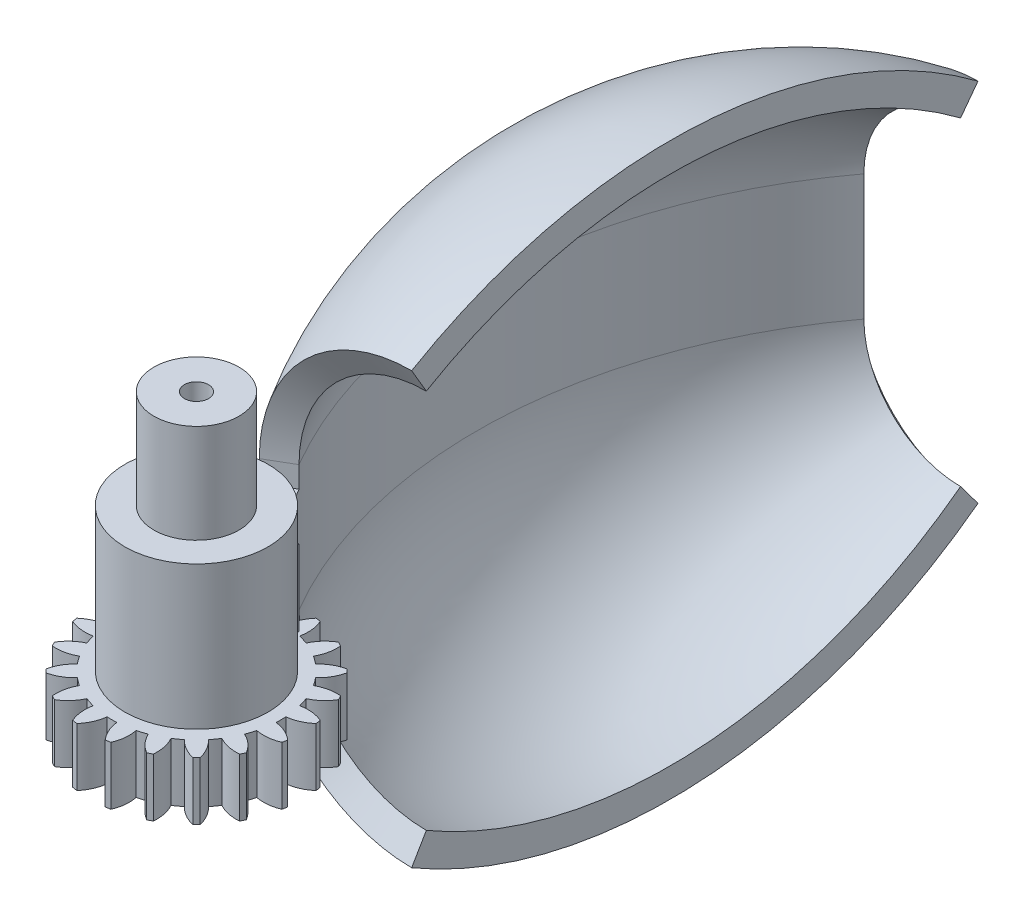
SolidWorks part; units mm, degrees
ref_plane "前视基准面" through (0, 0, 0) normal (0, 0, 1) x (1, 0, 0)
ref_plane "上视基准面" through (0, 0, 0) normal (0, 1, 0) x (1, 0, 0)
ref_plane "右视基准面" through (0, 0, 0) normal (1, 0, 0) x (0, 0, -1)
sketch "草图1" plane through (0, 0, 0) normal (0, 1, 0) x (1, 0, 0)
  line L0 (0, 0) -> (40, 0) construction
  line L1 (0, 42.7058) -> (0, -47.7896) construction
  line L2 (40, 0) -> (0, 30) construction
  line L3 (40, 0) -> (0, -30) construction
  line L4 (-2.4, 31.8) -> (0, 30)
  arc A0 (0, 30) -> (-1.3669, -28.0853) centre (40, 0) ccw
  arc A1 (-2.4, 31.8) -> (-5.7538, -26.7505) centre (40, 0) ccw
  arc A2 (-6.4737, -32.7477) -> (1.7806, -30.1779) centre (0, -39) ccw
  arc A3 (-6.4737, -32.7477) -> (-5.7538, -26.7505) centre (-10.0702, -29.2742) ccw
  arc A4 (1.7806, -30.1779) -> (-1.3669, -28.0853) centre (2.7698, -25.2767) cw
  circle A5 centre (0, -39) radius 1.25
  point P18 (0, -30)
  dimension "D4" = 18
  dimension "D5" = 5
  dimension "D6" = 5
  dimension "D7" = 2.5
  dimension "D1" = 60
  dimension "D2" = 40
  dimension "D3" = 53
extrude "凸台-拉伸2" add sketch "草图1" along normal blind 3
sketch "草图2" plane through (0, 3, 0) normal (0, 1, 0) x (1, 0, 0)
  line L0 (40, 0) -> (-5.7538, -26.7505) construction
  line L1 (-5.7538, -26.7505) -> (-3.1639, -25.2364)
  line L2 (-2.4, 31.8) -> (0, 30)
  line L3 (40, 0) -> (10, 0) construction
  line L4 (10, 9.7418) -> (10, -18.4807) construction
  arc A1 (0, 30) -> (-1.3669, -28.0853) centre (40, 0) ccw construction
  arc A2 (-2.4, 31.8) -> (-5.7538, -26.7505) centre (40, 0) ccw construction
  arc A4 (0, 30) -> (-3.1639, -25.2364) centre (40, 0) ccw
  arc A5 (-2.4, 31.8) -> (-5.7538, -26.7505) centre (40, 0) ccw
  dimension "13" = 30
extrude "凸台-拉伸6" add sketch "草图2" along normal blind 10
sketch "草图3" plane through (0, 0, 0) normal (0, -1, 0) x (1, 0, 0)
  line L0 (0, -30) -> (-2.4, -31.8) construction
  line L1 (0, -30) -> (-2.4, -31.8)
  line L2 (40, 0) -> (-5.7538, 26.7505) construction
  line L3 (-5.7538, 26.7505) -> (-3.1639, 25.2364)
  line L4 (40, 0) -> (10, 0) construction
  line L5 (10, 8.9651) -> (10, -7.6873) construction
  arc A0 (-5.7538, 26.7505) -> (-2.4, -31.8) centre (40, 0) ccw construction
  arc A1 (-1.3669, 28.0853) -> (0, -30) centre (40, 0) ccw construction
  arc A2 (-5.7538, 26.7505) -> (-2.4, -31.8) centre (40, 0) ccw
  arc A3 (-3.1639, 25.2364) -> (0, -30) centre (40, 0) ccw
  dimension "D1" = 30
revolve "旋转5" add sketch "草图3" angle 90 about L5
sketch "草图5" plane through (0, 3, 0) normal (0, 1, 0) x (1, 0, 0)
  circle A0 centre (0, -39) radius 7.4
  circle A1 centre (0, -39) radius 1.25 construction
  circle A2 centre (0, -39) radius 1.25
  dimension "D1" = 14.8
extrude "凸台-拉伸3" add sketch "草图5" along normal blind 14.8
sketch "草图6" plane through (0, 17.8, 0) normal (0, 1, 0) x (1, 0, 0)
  circle A0 centre (0, -39) radius 4.4
  circle A2 centre (0, -39) radius 1.25 construction
  circle A3 centre (0, -39) radius 1.25
  dimension "D1" = 8.8
  dimension "D2" = 2.5
extrude "凸台-拉伸4" add sketch "草图6" along normal blind 10.2
sketch "草图8" plane through (0, 13, 0) normal (0, 1, 0) x (1, 0, 0)
  line L0 (40, 0) -> (10, 0) construction
  line L1 (10, 0) -> (10, 11.1191) construction
  line L2 (0, 30) -> (-2.4, 31.8)
  line L3 (-5.7538, -26.7505) -> (-3.1639, -25.2364)
  line L4 (0, 30) -> (-2.4, 31.8)
  line L5 (-5.7538, -26.7505) -> (-3.1639, -25.2364)
  arc A2 (0, 30) -> (-3.1639, -25.2364) centre (40, 0) ccw
  arc A3 (-2.4, 31.8) -> (-5.7538, -26.7505) centre (40, 0) ccw
  arc A4 (0, 30) -> (-3.1639, -25.2364) centre (40, 0) ccw
  arc A5 (-2.4, 31.8) -> (-5.7538, -26.7505) centre (40, 0) ccw
  dimension "D2" = 30
  dimension "D1" = 0
revolve "旋转6" add sketch "草图8" angle 90 about L1
sketch "草图9" plane through (0, 3, 0) normal (0, 1, 0) x (1, 0, 0)
  line L0 (-5.3339, -33.8708) -> (-6.4737, -32.7477)
  line L1 (-3.1639, -25.2364) -> (-5.7538, -26.7505)
  line L2 (-3.1639, -25.2364) -> (-5.7538, -26.7505)
  line L3 (1.4703, -31.7475) -> (1.7806, -30.1779)
  circle A0 centre (0, -39) radius 7.4 construction
  arc A1 (1.4703, -31.7475) -> (-5.3339, -33.8708) centre (0, -39) ccw
  arc A4 (-6.4737, -32.7477) -> (-5.7538, -26.7505) centre (-10.0702, -29.2742) ccw
  arc A5 (-6.4737, -32.7477) -> (1.7806, -30.1779) centre (0, -39) ccw
  arc A6 (-1.3669, -28.0853) -> (1.7806, -30.1779) centre (2.7698, -25.2767) ccw
  arc A7 (-3.1639, -25.2364) -> (-1.3669, -28.0853) centre (40, 0) ccw
  arc A8 (-6.4737, -32.7477) -> (-5.7538, -26.7505) centre (-10.0702, -29.2742) ccw
  arc A10 (-1.3669, -28.0853) -> (1.7806, -30.1779) centre (2.7698, -25.2767) ccw
  arc A11 (-3.1639, -25.2364) -> (-1.3669, -28.0853) centre (40, 0) ccw
  dimension "D1" = 0
extrude "凸台-拉伸7" add sketch "草图9" along normal blind 7.8
sketch "草图12" plane through (0, 0, 0) normal (0, -1, 0) x (1, 0, 0)
  line L4 (-6.4737, 32.7477) -> (0, 39)
  line L5 (0, 39) -> (1.7806, 30.1779)
  arc A4 (1.7806, 30.1779) -> (-6.4737, 32.7477) centre (0, 39) ccw construction
  arc A5 (1.7806, 30.1779) -> (-6.4737, 32.7477) centre (0, 39) ccw
extrude "切除-拉伸1" cut sketch "草图12" against normal blind 3
sketch "草图14" plane through (0, 0, 0) normal (0, -1, 0) x (1, 0, 0)
  line L0 (-6.4737, 32.7477) -> (1.7806, 30.1779)
  line L4 (1.7806, 30.1779) -> (0.2473, 37.7747)
  line L5 (-5.7538, 26.7505) -> (-3.1639, 25.2364)
  line L8 (-5.7538, 26.7505) -> (-3.1639, 25.2364)
  line L9 (1.7806, 30.1779) -> (0.2473, 37.7747) construction
  line L10 (-0.8991, 38.1316) -> (-6.4737, 32.7477)
  line L11 (-0.8991, 38.1316) -> (-6.4737, 32.7477) construction
  arc A4 (1.7806, 30.1779) -> (-1.3669, 28.0853) centre (2.7698, 25.2767) ccw
  arc A5 (-0.8991, 38.1316) -> (0.2473, 37.7747) centre (0, 39) ccw
  arc A6 (-5.7538, 26.7505) -> (-6.4737, 32.7477) centre (-10.0702, 29.2742) ccw
  arc A7 (-1.3669, 28.0853) -> (-3.1639, 25.2364) centre (40, 0) ccw
  arc A8 (1.7806, 30.1779) -> (-1.3669, 28.0853) centre (2.7698, 25.2767) ccw
  arc A10 (-5.7538, 26.7505) -> (-6.4737, 32.7477) centre (-10.0702, 29.2742) ccw
  arc A11 (-1.3669, 28.0853) -> (-3.1639, 25.2364) centre (40, 0) ccw
  arc A12 (-0.8991, 38.1316) -> (0.2473, 37.7747) centre (0, 39) ccw construction
  dimension "D1" = 0
extrude "凸台-拉伸9" add sketch "草图14" along normal blind 3
sketch "草图13" plane through (0, 0, 0) normal (0, -1, 0) x (1, 0, 0)
  arc A240 (1.465, 49.902) -> (0.4999, 47.7347) centre (4.4722, 47.2645) ccw
  arc A241 (0.4999, 47.7347) -> (-0.4999, 47.7347) centre (0, 39) ccw
  arc A242 (-0.4999, 47.7347) -> (-1.465, 49.902) centre (-4.4722, 47.2645) ccw
  arc A243 (-1.465, 49.902) -> (-1.9757, 49.8211) centre (0, 39) ccw
  arc A244 (-1.9757, 49.8211) -> (-2.2237, 47.4617) centre (1.6994, 48.242) ccw
  arc A245 (-2.2237, 47.4617) -> (-3.1746, 47.1527) centre (0, 39) ccw
  arc A246 (-3.1746, 47.1527) -> (-4.7622, 48.9157) centre (-6.8072, 45.478) ccw
  arc A247 (-4.7622, 48.9157) -> (-5.2229, 48.681) centre (0, 39) ccw
  arc A248 (-5.2229, 48.681) -> (-4.7297, 46.3604) centre (-1.2397, 48.3148) ccw
  arc A249 (-4.7297, 46.3604) -> (-5.5386, 45.7727) centre (0, 39) ccw
  arc A250 (-5.5386, 45.7727) -> (-7.5932, 46.9588) centre (-8.4758, 43.0574) ccw
  arc A251 (-7.5932, 46.9588) -> (-7.9588, 46.5932) centre (0, 39) ccw
  arc A252 (-7.9588, 46.5932) -> (-6.7727, 44.5386) centre (-4.0574, 47.4758) ccw
  arc A253 (-6.7727, 44.5386) -> (-7.3604, 43.7297) centre (0, 39) ccw
  arc A254 (-7.3604, 43.7297) -> (-9.681, 44.2229) centre (-9.3148, 40.2397) ccw
  arc A255 (-9.681, 44.2229) -> (-9.9157, 43.7622) centre (0, 39) ccw
  arc A256 (-9.9157, 43.7622) -> (-8.1527, 42.1746) centre (-6.478, 45.8072) ccw
  arc A257 (-8.1527, 42.1746) -> (-8.4617, 41.2237) centre (0, 39) ccw
  arc A258 (-8.4617, 41.2237) -> (-10.8211, 40.9757) centre (-9.242, 37.3006) ccw
  arc A259 (-10.8211, 40.9757) -> (-10.902, 40.465) centre (0, 39) ccw
  arc A260 (-10.902, 40.465) -> (-8.7347, 39.4999) centre (-8.2645, 43.4722) ccw
  arc A261 (-8.7347, 39.4999) -> (-8.7347, 38.5001) centre (0, 39) ccw
  arc A262 (-8.7347, 38.5001) -> (-10.902, 37.535) centre (-8.2645, 34.5278) ccw
  arc A263 (-10.902, 37.535) -> (-10.8211, 37.0243) centre (0, 39) ccw
  arc A264 (-10.8211, 37.0243) -> (-8.4617, 36.7763) centre (-9.242, 40.6994) ccw
  arc A265 (-8.4617, 36.7763) -> (-8.1527, 35.8254) centre (0, 39) ccw
  arc A266 (-8.1527, 35.8254) -> (-9.9157, 34.2378) centre (-6.478, 32.1928) ccw
  arc A267 (-9.9157, 34.2378) -> (-9.681, 33.7771) centre (0, 39) ccw
  arc A268 (-9.681, 33.7771) -> (-7.3604, 34.2703) centre (-9.3148, 37.7603) ccw
  arc A269 (-7.3604, 34.2703) -> (-6.7727, 33.4614) centre (0, 39) ccw
  arc A270 (-6.7727, 33.4614) -> (-7.9588, 31.4068) centre (-4.0574, 30.5242) ccw
  arc A271 (-7.9588, 31.4068) -> (-7.5932, 31.0412) centre (0, 39) ccw
  arc A272 (-7.5932, 31.0412) -> (-5.5386, 32.2273) centre (-8.4758, 34.9426) ccw
  arc A273 (-5.5386, 32.2273) -> (-4.7297, 31.6396) centre (0, 39) ccw
  arc A274 (-4.7297, 31.6396) -> (-5.2229, 29.319) centre (-1.2397, 29.6852) ccw
  arc A275 (-5.2229, 29.319) -> (-4.7622, 29.0843) centre (0, 39) ccw
  arc A276 (-4.7622, 29.0843) -> (-3.1746, 30.8473) centre (-6.8072, 32.522) ccw
  arc A277 (-3.1746, 30.8473) -> (-2.2237, 30.5383) centre (0, 39) ccw
  arc A278 (-2.2237, 30.5383) -> (-1.9757, 28.1789) centre (1.6994, 29.758) ccw
  arc A279 (-1.9757, 28.1789) -> (-1.465, 28.098) centre (0, 39) ccw
  arc A280 (-1.465, 28.098) -> (-0.4999, 30.2653) centre (-4.4722, 30.7355) ccw
  arc A281 (-0.4999, 30.2653) -> (0.4999, 30.2653) centre (0, 39) ccw
  arc A282 (0.4999, 30.2653) -> (1.465, 28.098) centre (4.4722, 30.7355) ccw
  arc A283 (1.465, 28.098) -> (1.9757, 28.1789) centre (0, 39) ccw
  arc A284 (1.9757, 28.1789) -> (2.2237, 30.5383) centre (-1.6994, 29.758) ccw
  arc A285 (2.2237, 30.5383) -> (3.1746, 30.8473) centre (0, 39) ccw
  arc A286 (3.1746, 30.8473) -> (4.7622, 29.0843) centre (6.8072, 32.522) ccw
  arc A287 (4.7622, 29.0843) -> (5.2229, 29.319) centre (0, 39) ccw
  arc A288 (5.2229, 29.319) -> (4.7297, 31.6396) centre (1.2397, 29.6852) ccw
  arc A289 (4.7297, 31.6396) -> (5.5386, 32.2273) centre (0, 39) ccw
  arc A290 (5.5386, 32.2273) -> (7.5932, 31.0412) centre (8.4758, 34.9426) ccw
  arc A291 (7.5932, 31.0412) -> (7.9588, 31.4068) centre (0, 39) ccw
  arc A292 (7.9588, 31.4068) -> (6.7727, 33.4614) centre (4.0574, 30.5242) ccw
  arc A293 (6.7727, 33.4614) -> (7.3604, 34.2703) centre (0, 39) ccw
  arc A294 (7.3604, 34.2703) -> (9.681, 33.7771) centre (9.3148, 37.7603) ccw
  arc A295 (9.681, 33.7771) -> (9.9157, 34.2378) centre (0, 39) ccw
  arc A296 (9.9157, 34.2378) -> (8.1527, 35.8254) centre (6.478, 32.1928) ccw
  arc A297 (8.1527, 35.8254) -> (8.4617, 36.7763) centre (0, 39) ccw
  arc A298 (8.4617, 36.7763) -> (10.8211, 37.0243) centre (9.242, 40.6994) ccw
  arc A299 (10.8211, 37.0243) -> (10.902, 37.535) centre (0, 39) ccw
  arc A300 (10.902, 37.535) -> (8.7347, 38.5001) centre (8.2645, 34.5278) ccw
  arc A301 (8.7347, 38.5001) -> (8.7347, 39.4999) centre (0, 39) ccw
  arc A302 (8.7347, 39.4999) -> (10.902, 40.465) centre (8.2645, 43.4722) ccw
  arc A303 (10.902, 40.465) -> (10.8211, 40.9757) centre (0, 39) ccw
  arc A304 (10.8211, 40.9757) -> (8.4617, 41.2237) centre (9.242, 37.3006) ccw
  arc A305 (8.4617, 41.2237) -> (8.1527, 42.1746) centre (0, 39) ccw
  arc A306 (8.1527, 42.1746) -> (9.9157, 43.7622) centre (6.478, 45.8072) ccw
  arc A307 (9.9157, 43.7622) -> (9.681, 44.2229) centre (0, 39) ccw
  arc A308 (9.681, 44.2229) -> (7.3604, 43.7297) centre (9.3148, 40.2397) ccw
  arc A309 (7.3604, 43.7297) -> (6.7727, 44.5386) centre (0, 39) ccw
  arc A310 (6.7727, 44.5386) -> (7.9588, 46.5932) centre (4.0574, 47.4758) ccw
  arc A311 (7.9588, 46.5932) -> (7.5932, 46.9588) centre (0, 39) ccw
  arc A312 (7.5932, 46.9588) -> (5.5386, 45.7727) centre (8.4758, 43.0574) ccw
  arc A313 (5.5386, 45.7727) -> (4.7297, 46.3604) centre (0, 39) ccw
  arc A314 (4.7297, 46.3604) -> (5.2229, 48.681) centre (1.2397, 48.3148) ccw
  arc A315 (5.2229, 48.681) -> (4.7622, 48.9157) centre (0, 39) ccw
  arc A316 (4.7622, 48.9157) -> (3.1746, 47.1527) centre (6.8072, 45.478) ccw
  arc A317 (3.1746, 47.1527) -> (2.2237, 47.4617) centre (0, 39) ccw
  arc A318 (2.2237, 47.4617) -> (1.9757, 49.8211) centre (-1.6994, 48.242) ccw
  arc A319 (1.9757, 49.8211) -> (1.465, 49.902) centre (0, 39) ccw
  arc A320 (1.465, 49.902) -> (0.4999, 47.7347) centre (4.4722, 47.2645) ccw
  arc A321 (0.4999, 47.7347) -> (-0.4999, 47.7347) centre (0, 39) ccw
  arc A322 (-0.4999, 47.7347) -> (-1.465, 49.902) centre (-4.4722, 47.2645) ccw
  arc A323 (-1.465, 49.902) -> (-1.9757, 49.8211) centre (0, 39) ccw
  arc A324 (-1.9757, 49.8211) -> (-2.2237, 47.4617) centre (1.6994, 48.242) ccw
  arc A325 (-2.2237, 47.4617) -> (-3.1746, 47.1527) centre (0, 39) ccw
  arc A326 (-3.1746, 47.1527) -> (-4.7622, 48.9157) centre (-6.8072, 45.478) ccw
  arc A327 (-4.7622, 48.9157) -> (-5.2229, 48.681) centre (0, 39) ccw
  arc A328 (-5.2229, 48.681) -> (-4.7297, 46.3604) centre (-1.2397, 48.3148) ccw
  arc A329 (-4.7297, 46.3604) -> (-5.5386, 45.7727) centre (0, 39) ccw
  arc A330 (-5.5386, 45.7727) -> (-7.5932, 46.9588) centre (-8.4758, 43.0574) ccw
  arc A331 (-7.5932, 46.9588) -> (-7.9588, 46.5932) centre (0, 39) ccw
  arc A332 (-7.9588, 46.5932) -> (-6.7727, 44.5386) centre (-4.0574, 47.4758) ccw
  arc A333 (-6.7727, 44.5386) -> (-7.3604, 43.7297) centre (0, 39) ccw
  arc A334 (-7.3604, 43.7297) -> (-9.681, 44.2229) centre (-9.3148, 40.2397) ccw
  arc A335 (-9.681, 44.2229) -> (-9.9157, 43.7622) centre (0, 39) ccw
  arc A336 (-9.9157, 43.7622) -> (-8.1527, 42.1746) centre (-6.478, 45.8072) ccw
  arc A337 (-8.1527, 42.1746) -> (-8.4617, 41.2237) centre (0, 39) ccw
  arc A338 (-8.4617, 41.2237) -> (-10.8211, 40.9757) centre (-9.242, 37.3006) ccw
  arc A339 (-10.8211, 40.9757) -> (-10.902, 40.465) centre (0, 39) ccw
  arc A340 (-10.902, 40.465) -> (-8.7347, 39.4999) centre (-8.2645, 43.4722) ccw
  arc A341 (-8.7347, 39.4999) -> (-8.7347, 38.5001) centre (0, 39) ccw
  arc A342 (-8.7347, 38.5001) -> (-10.902, 37.535) centre (-8.2645, 34.5278) ccw
  arc A343 (-10.902, 37.535) -> (-10.8211, 37.0243) centre (0, 39) ccw
  arc A344 (-10.8211, 37.0243) -> (-8.4617, 36.7763) centre (-9.242, 40.6994) ccw
  arc A345 (-8.4617, 36.7763) -> (-8.1527, 35.8254) centre (0, 39) ccw
  arc A346 (-8.1527, 35.8254) -> (-9.9157, 34.2378) centre (-6.478, 32.1928) ccw
  arc A347 (-9.9157, 34.2378) -> (-9.681, 33.7771) centre (0, 39) ccw
  arc A348 (-9.681, 33.7771) -> (-7.3604, 34.2703) centre (-9.3148, 37.7603) ccw
  arc A349 (-7.3604, 34.2703) -> (-6.7727, 33.4614) centre (0, 39) ccw
  arc A350 (-6.7727, 33.4614) -> (-7.9588, 31.4068) centre (-4.0574, 30.5242) ccw
  arc A351 (-7.9588, 31.4068) -> (-7.5932, 31.0412) centre (0, 39) ccw
  arc A352 (-7.5932, 31.0412) -> (-5.5386, 32.2273) centre (-8.4758, 34.9426) ccw
  arc A353 (-5.5386, 32.2273) -> (-4.7297, 31.6396) centre (0, 39) ccw
  arc A354 (-4.7297, 31.6396) -> (-5.2229, 29.319) centre (-1.2397, 29.6852) ccw
  arc A355 (-5.2229, 29.319) -> (-4.7622, 29.0843) centre (0, 39) ccw
  arc A356 (-4.7622, 29.0843) -> (-3.1746, 30.8473) centre (-6.8072, 32.522) ccw
  arc A357 (-3.1746, 30.8473) -> (-2.2237, 30.5383) centre (0, 39) ccw
  arc A358 (-2.2237, 30.5383) -> (-1.9757, 28.1789) centre (1.6994, 29.758) ccw
  arc A359 (-1.9757, 28.1789) -> (-1.465, 28.098) centre (0, 39) ccw
  arc A360 (-1.465, 28.098) -> (-0.4999, 30.2653) centre (-4.4722, 30.7355) ccw
  arc A361 (-0.4999, 30.2653) -> (0.4999, 30.2653) centre (0, 39) ccw
  arc A362 (0.4999, 30.2653) -> (1.465, 28.098) centre (4.4722, 30.7355) ccw
  arc A363 (1.465, 28.098) -> (1.9757, 28.1789) centre (0, 39) ccw
  arc A364 (1.9757, 28.1789) -> (2.2237, 30.5383) centre (-1.6994, 29.758) ccw
  arc A365 (2.2237, 30.5383) -> (3.1746, 30.8473) centre (0, 39) ccw
  arc A366 (3.1746, 30.8473) -> (4.7622, 29.0843) centre (6.8072, 32.522) ccw
  arc A367 (4.7622, 29.0843) -> (5.2229, 29.319) centre (0, 39) ccw
  arc A368 (5.2229, 29.319) -> (4.7297, 31.6396) centre (1.2397, 29.6852) ccw
  arc A369 (4.7297, 31.6396) -> (5.5386, 32.2273) centre (0, 39) ccw
  arc A370 (5.5386, 32.2273) -> (7.5932, 31.0412) centre (8.4758, 34.9426) ccw
  arc A371 (7.5932, 31.0412) -> (7.9588, 31.4068) centre (0, 39) ccw
  arc A372 (7.9588, 31.4068) -> (6.7727, 33.4614) centre (4.0574, 30.5242) ccw
  arc A373 (6.7727, 33.4614) -> (7.3604, 34.2703) centre (0, 39) ccw
  arc A374 (7.3604, 34.2703) -> (9.681, 33.7771) centre (9.3148, 37.7603) ccw
  arc A375 (9.681, 33.7771) -> (9.9157, 34.2378) centre (0, 39) ccw
  arc A376 (9.9157, 34.2378) -> (8.1527, 35.8254) centre (6.478, 32.1928) ccw
  arc A377 (8.1527, 35.8254) -> (8.4617, 36.7763) centre (0, 39) ccw
  arc A378 (8.4617, 36.7763) -> (10.8211, 37.0243) centre (9.242, 40.6994) ccw
  arc A379 (10.8211, 37.0243) -> (10.902, 37.535) centre (0, 39) ccw
  arc A380 (10.902, 37.535) -> (8.7347, 38.5001) centre (8.2645, 34.5278) ccw
  arc A381 (8.7347, 38.5001) -> (8.7347, 39.4999) centre (0, 39) ccw
  arc A382 (8.7347, 39.4999) -> (10.902, 40.465) centre (8.2645, 43.4722) ccw
  arc A383 (10.902, 40.465) -> (10.8211, 40.9757) centre (0, 39) ccw
  arc A384 (10.8211, 40.9757) -> (8.4617, 41.2237) centre (9.242, 37.3006) ccw
  arc A385 (8.4617, 41.2237) -> (8.1527, 42.1746) centre (0, 39) ccw
  arc A386 (8.1527, 42.1746) -> (9.9157, 43.7622) centre (6.478, 45.8072) ccw
  arc A387 (9.9157, 43.7622) -> (9.681, 44.2229) centre (0, 39) ccw
  arc A388 (9.681, 44.2229) -> (7.3604, 43.7297) centre (9.3148, 40.2397) ccw
  arc A389 (7.3604, 43.7297) -> (6.7727, 44.5386) centre (0, 39) ccw
  arc A390 (6.7727, 44.5386) -> (7.9588, 46.5932) centre (4.0574, 47.4758) ccw
  arc A391 (7.9588, 46.5932) -> (7.5932, 46.9588) centre (0, 39) ccw
  arc A392 (7.5932, 46.9588) -> (5.5386, 45.7727) centre (8.4758, 43.0574) ccw
  arc A393 (5.5386, 45.7727) -> (4.7297, 46.3604) centre (0, 39) ccw
  arc A394 (4.7297, 46.3604) -> (5.2229, 48.681) centre (1.2397, 48.3148) ccw
  arc A395 (5.2229, 48.681) -> (4.7622, 48.9157) centre (0, 39) ccw
  arc A396 (4.7622, 48.9157) -> (3.1746, 47.1527) centre (6.8072, 45.478) ccw
  arc A397 (3.1746, 47.1527) -> (2.2237, 47.4617) centre (0, 39) ccw
  arc A398 (2.2237, 47.4617) -> (1.9757, 49.8211) centre (-1.6994, 48.242) ccw
  arc A399 (1.9757, 49.8211) -> (1.465, 49.902) centre (0, 39) ccw
  dimension "D1" = 0
extrude "凸台-拉伸10" add sketch "草图13" along normal mid plane 6
